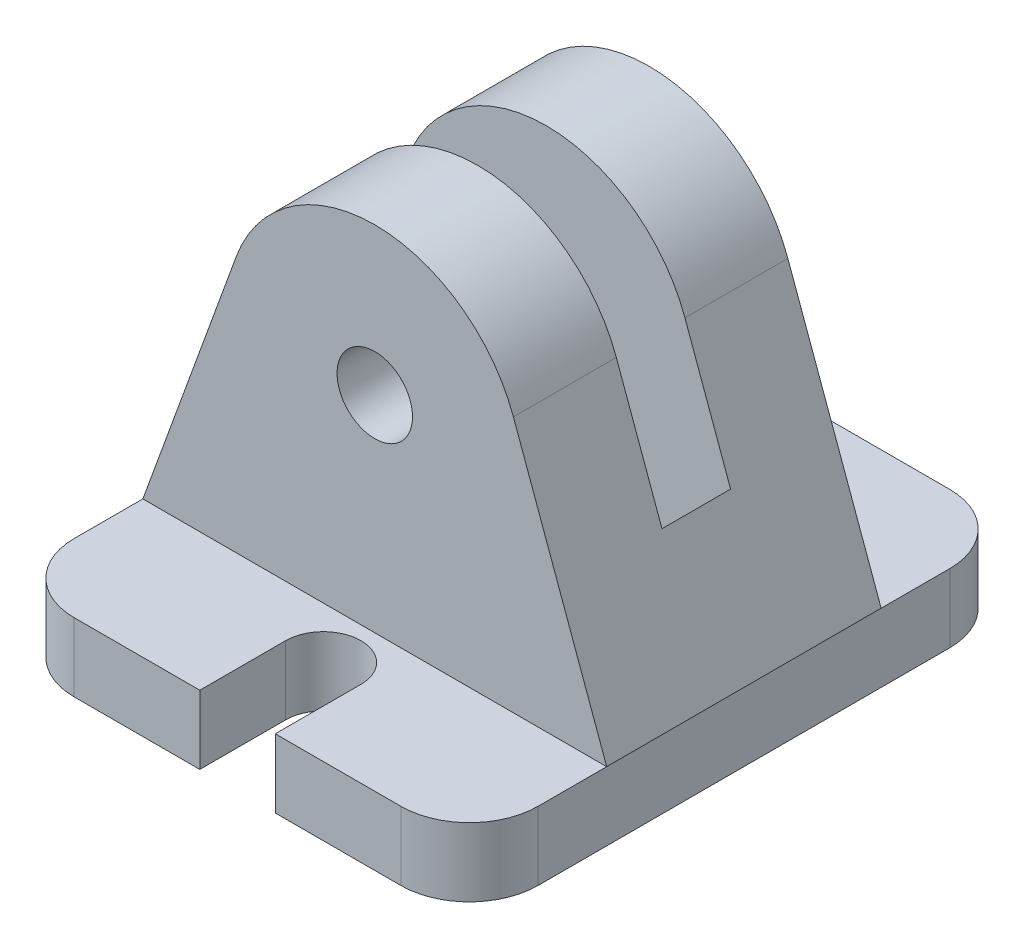
SolidWorks part; units mm, degrees
ref_plane "Front Plane" through (0, 0, 0) normal (0, 0, 1) x (1, 0, 0)
ref_plane "Top Plane" through (0, 0, 0) normal (0, 1, 0) x (1, 0, 0)
ref_plane "Right Plane" through (0, 0, 0) normal (1, 0, 0) x (0, 0, -1)
sketch "Sketch1" plane through (0, 0, 0) normal (0, 0, 1) x (1, 0, 0)
  line L0 (-10.1017, 3.6767) -> (-16.8995, -15)
  line L1 (-16.8995, -15) -> (16.8995, -15)
  line L2 (16.8995, -15) -> (10.1017, 3.6767)
  line L3 (0, 0) -> (0, -8346.2782) construction
  arc A0 (10.1017, 3.6767) -> (-10.1017, 3.6767) centre (0, 0) ccw
  circle A1 centre (0, 0) radius 2.75
  dimension "D1" = 5.5
  dimension "D2" = 8
  dimension "D3" = 20
  dimension "D4" = 15
extrude "Boss-Extrude1" add sketch "Sketch1" along normal mid plane 20
sketch "Sketch2" plane through (0, 0, 0) normal (0, 0, 1) x (1, 0, 0)
  circle A0 centre (0, 0) radius 14.5
  dimension "D1" = 29
extrude "Cut-Extrude1" cut sketch "Sketch2" against normal mid plane 5
sketch "Sketch3" plane through (0, -15, 0) normal (0, -1, 0) x (1, 0, 0)
  line L0 (0, 0) -> (50000, 0) construction
  line L1 (-16.8995, 10) -> (16.8995, 10)
  line L2 (-16.8995, 10) -> (-16.8995, 15)
  line L3 (-11.8995, 20) -> (11.8995, 20)
  line L4 (16.8995, 10) -> (16.8995, 15)
  line L5 (16.8995, -10) -> (16.8995, -15)
  line L6 (-11.8995, -20) -> (11.8995, -20)
  line L7 (-16.8995, -10) -> (-16.8995, -15)
  line L8 (-16.8995, -10) -> (16.8995, -10)
  line L9 (16.8995, 10) -> (16.8995, -10) construction
  line L11 (-16.8995, 10) -> (16.8995, 10)
  line L12 (-16.8995, 10) -> (-16.8995, -10)
  line L13 (-16.8995, -10) -> (16.8995, -10)
  line L14 (16.8995, 10) -> (16.8995, -10)
  arc A0 (11.8995, 20) -> (16.8995, 15) centre (11.8995, 15) cw
  arc A1 (-16.8995, 15) -> (-11.8995, 20) centre (-11.8995, 15) cw
  arc A2 (-16.8995, -15) -> (-11.8995, -20) centre (-11.8995, -15) ccw
  arc A3 (11.8995, -20) -> (16.8995, -15) centre (11.8995, -15) ccw
  line M4 (-16.8995, -10) -> (16.8995, -10)
  line M5 (16.8995, -10) -> (16.8995, 10)
  line M6 (16.8995, 10) -> (-16.8995, 10)
  line M7 (-16.8995, 10) -> (-16.8995, -10)
  dimension "D1" = 5
  dimension "D2" = 10
extrude "Boss-Extrude2" add sketch "Sketch3" along normal blind 5 contours A1 L2 L4 A0 L3 M6 | L0 L14 M7 M6 | L0 L12 M4 M5 | L6 A3 L5 L7 A2 M4
sketch "Sketch4" plane through (0, -20, 0) normal (0, -1, 0) x (1, 0, 0)
  line L0 (-2.75, 20) -> (-2.75, 13.75)
  line L1 (-11.8995, 20) -> (11.8995, 20) construction
  line L2 (-2.75, 13.75) -> (2.75, 13.75) construction
  line L3 (2.75, 13.75) -> (2.75, 20)
  line L4 (0, 0) -> (0, -50000) construction
  line L5 (-16.8995, 10) -> (16.8995, 10) construction
  line L6 (0, 0) -> (50000, 0) construction
  line L7 (-2.75, 20) -> (2.75, 20)
  line L8 (-2.75, -20) -> (-2.75, -13.75)
  line L9 (2.75, -13.75) -> (2.75, -20)
  line L10 (-2.75, -20) -> (2.75, -20)
  arc A0 (-2.75, 13.75) -> (2.75, 13.75) centre (0, 13.75) ccw
  arc A1 (-2.75, -13.75) -> (2.75, -13.75) centre (0, -13.75) cw
  dimension "D1" = 5.5
  dimension "D2" = 3.75
extrude "Cut-Extrude5" cut sketch "Sketch4" against normal through all
sketch "Sketch5" plane through (0, 0, 0) normal (0, 0, 1) x (1, 0, 0)
  line L0 (-10.253, 10.253) -> (-31.4663, -10.9602)
  line L1 (-31.4663, -10.9602) -> (-10.9602, -31.4663)
  line L2 (-10.9602, -31.4663) -> (10.253, -10.253)
  line L3 (-16.8995, -15) -> (16.8995, -15) construction
  circle A0 centre (0, 0) radius 14.5
  arc A1 (-13.4298, -5.4672) -> (13.4298, -5.4672) centre (0, 0) ccw construction
  dimension "D1" = 30
  dimension "D2" = 45
extrude "Cut-Extrude6" cut sketch "Sketch5" against normal mid plane 5 contours A0 | A0 L0 L1 L2
